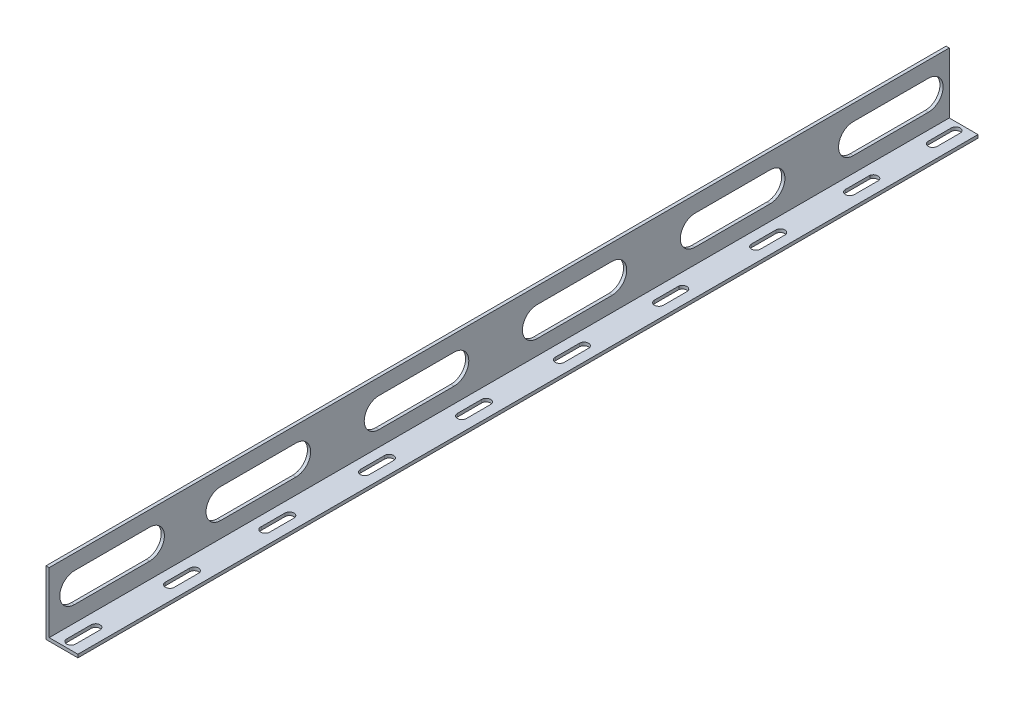
SolidWorks part; units mm, degrees
ref_plane "Front Plane" through (0, 0, 0) normal (0, 0, 1) x (1, 0, 0)
ref_plane "Top Plane" through (0, 0, 0) normal (0, 1, 0) x (1, 0, 0)
ref_plane "Right Plane" through (0, 0, 0) normal (1, 0, 0) x (0, 0, -1)
sketch "Sketch1" plane through (0, 0, 0) normal (0, 0, 1) x (1, 0, 0)
  line L0 (-9.4515, 23.8095) -> (-9.4515, -26.1905)
  line L1 (-9.4515, -26.1905) -> (15.5485, -26.1905)
  line L2 (15.5485, -26.1905) -> (15.5485, -23.6905)
  line L3 (15.5485, -23.6905) -> (-6.9515, -23.6905)
  line L4 (-6.9515, -23.6905) -> (-6.9515, 23.8095)
  line L5 (-6.9515, 23.8095) -> (-9.4515, 23.8095)
  dimension "D1" = 2.5
  dimension "D2" = 2.5
  dimension "D3" = 50
  dimension "D4" = 25
extrude "Boss-Extrude1" add sketch "Sketch1" along normal blind 705
sketch "Sketch2" plane through (-6.9515, 0, 0) normal (1, 0, 0) x (0, 0, -1)
  line L0 (-710.1986, -0.1555) -> (-0.1986, -0.215) construction
  line L1 (-685.1732, 11.8665) -> (-626.2752, 11.8665)
  line L3 (-626.2752, -11.1449) -> (-685.1732, -11.1449)
  line L4 (-570.643, 11.6317) -> (-511.7449, 11.6317)
  line L5 (-511.7449, -11.3796) -> (-570.643, -11.3796)
  line L6 (-446.7449, 11.3483) -> (-387.8469, 11.3483)
  line L7 (-387.8469, -11.6631) -> (-446.7449, -11.6631)
  line L9 (-322.8469, 11.0878) -> (-263.9488, 11.0878)
  line L10 (-263.9488, -11.9236) -> (-322.8469, -11.9236)
  line L11 (-199.1228, 11.2603) -> (-140.2248, 11.2603)
  line L12 (-140.2248, -11.7511) -> (-199.1228, -11.7511)
  line L13 (-75.2248, 11.4022) -> (-16.3267, 11.4022)
  line L14 (-16.3267, -11.6092) -> (-75.2248, -11.6092)
  arc A21 (-685.1732, -11.1449) -> (-685.1732, 11.8665) centre (-685.1732, 0.3608) cw
  arc A22 (-626.2752, 11.8665) -> (-626.2752, -11.1449) centre (-626.2752, 0.3608) cw
  arc A23 (-570.643, -11.3796) -> (-570.643, 11.6317) centre (-570.643, 0.1261) cw
  arc A24 (-511.7449, 11.6317) -> (-511.7449, -11.3796) centre (-511.7449, 0.1261) cw
  arc A25 (-446.7449, -11.6631) -> (-446.7449, 11.3483) centre (-446.7449, -0.1574) cw
  arc A26 (-387.8469, 11.3483) -> (-387.8469, -11.6631) centre (-387.8469, -0.1574) cw
  arc A27 (-322.8469, -11.9236) -> (-322.8469, 11.0878) centre (-322.8469, -0.4179) cw
  arc A28 (-263.9488, 11.0878) -> (-263.9488, -11.9236) centre (-264.1228, -0.4179) cw
  arc A29 (-199.1228, -11.7511) -> (-199.1228, 11.2603) centre (-199.1228, -0.2454) cw
  arc A30 (-140.2248, 11.2603) -> (-140.2248, -11.7511) centre (-140.2248, -0.2454) cw
  arc A31 (-75.2248, -11.6092) -> (-75.2248, 11.4022) centre (-75.2248, -0.1035) cw
  arc A32 (-16.3267, 11.4022) -> (-16.3267, -11.6092) centre (-16.3267, -0.1035) cw
  dimension "D2" = 65
  dimension "D4" = 65
  dimension "D5" = 65
  dimension "D6" = 65
sketch "Sketch3" plane through (0, -23.6905, 0) normal (0, 1, 0) x (1, 0, 0)
  line L0 (4.2985, -705) -> (4.2985, 0) construction
  line L2 (15.5485, 0) -> (-6.9515, 0) construction
  line L8 (1.1, -238.9216) -> (1.1, -219.9216)
  line L9 (8.1, -238.9216) -> (8.1, -219.9216)
  line L12 (1.0628, -162.8147) -> (1.0637, -143.8147)
  line L13 (8.0647, -162.8172) -> (8.0637, -143.8172)
  line L14 (0.5839, -24.0036) -> (0.5839, -6.0036)
  line L15 (7.5839, -24.0036) -> (7.5839, -6.0036)
  line L16 (15.5485, -705) -> (-6.9515, -705) construction
  line L17 (0.9993, -316.47) -> (0.9993, -297.47)
  line L18 (7.9993, -316.47) -> (7.9993, -297.47)
  line L21 (0.7939, -392.9452) -> (0.7939, -373.9452)
  line L22 (7.7939, -392.9452) -> (7.7939, -373.9452)
  line L25 (0.8067, -468.9764) -> (0.8067, -449.9764)
  line L26 (7.8067, -468.9764) -> (7.8067, -449.9764)
  line L29 (0.8388, -546.5768) -> (0.8388, -528.0239)
  line L30 (7.8388, -546.5768) -> (7.8388, -528.0239)
  line L31 (0.8883, -621.7812) -> (0.8883, -602.7812)
  line L32 (7.8883, -621.7812) -> (7.8883, -602.7812)
  line L33 (0.7548, -698.919) -> (0.7548, -679.919)
  line L34 (7.7548, -698.919) -> (7.7548, -679.919)
  line L35 (0.8388, -89.0655) -> (0.8388, -70.0655)
  line L36 (7.8388, -89.0655) -> (7.8388, -70.0655)
  arc A6 (1.1, -238.9216) -> (8.1, -238.9216) centre (4.6, -239.0026) ccw
  arc A7 (1.1, -219.9216) -> (8.1, -219.9216) centre (4.6, -220.6284) cw
  arc A10 (1.0628, -162.8147) -> (8.0647, -162.8172) centre (4.5637, -162.9587) ccw
  arc A11 (1.0637, -143.8147) -> (8.0637, -143.8172) centre (4.5637, -143.8159) cw
  arc A14 (0.5839, -6.0036) -> (7.5839, -6.0036) centre (4.0839, -6.0036) cw
  arc A15 (0.5839, -24.0036) -> (7.5839, -24.0036) centre (4.0839, -24.0036) ccw
  arc A16 (0.9993, -316.47) -> (7.9993, -316.47) centre (4.4993, -316.551) ccw
  arc A17 (0.9993, -297.47) -> (7.9993, -297.47) centre (4.4993, -297.5188) cw
  arc A20 (0.7939, -392.9452) -> (7.7939, -392.9452) centre (4.2939, -393.0262) ccw
  arc A21 (0.7939, -373.9452) -> (7.7939, -373.9452) centre (4.2939, -373.994) cw
  arc A24 (0.8067, -468.9764) -> (7.8067, -468.9764) centre (4.3067, -469.0574) ccw
  arc A25 (0.8067, -449.9764) -> (7.8067, -449.9764) centre (4.3067, -450.0251) cw
  arc A28 (0.8388, -546.5768) -> (7.8388, -546.5768) centre (4.3388, -547.1049) ccw
  arc A29 (0.8388, -528.0239) -> (7.8388, -528.0239) centre (4.3388, -528.0727) cw
  arc A30 (0.8883, -621.7812) -> (7.8883, -621.7812) centre (4.3883, -621.8622) ccw
  arc A31 (0.8883, -602.7812) -> (7.8883, -602.7812) centre (4.3883, -602.83) cw
  arc A32 (0.7548, -698.919) -> (7.7548, -698.919) centre (4.2548, -699) ccw
  arc A33 (0.7548, -679.919) -> (7.7548, -679.919) centre (4.2548, -679.8622) cw
  arc A34 (0.8388, -89.0655) -> (7.8388, -89.0655) centre (4.3388, -89.1465) ccw
  arc A35 (0.8388, -70.0655) -> (7.8388, -70.0655) centre (4.3388, -70.7723) cw
  point P13 (0, 0)
  point P14 (0, 0)
  point P15 (0, 0)
  point P16 (4.2985, -705)
  dimension "D1" = 7
  dimension "D2" = 18
  dimension "D3" = 18
  dimension "D4" = 7
  dimension "D5" = 19
  dimension "D6" = 19
  dimension "D11" = 6
  dimension "D12" = 58
  dimension "D13" = 19
extrude "Cut-Extrude2" cut sketch "Sketch3" against normal blind 10
extrude "Cut-Extrude3" cut sketch "Sketch2" against normal blind 10
